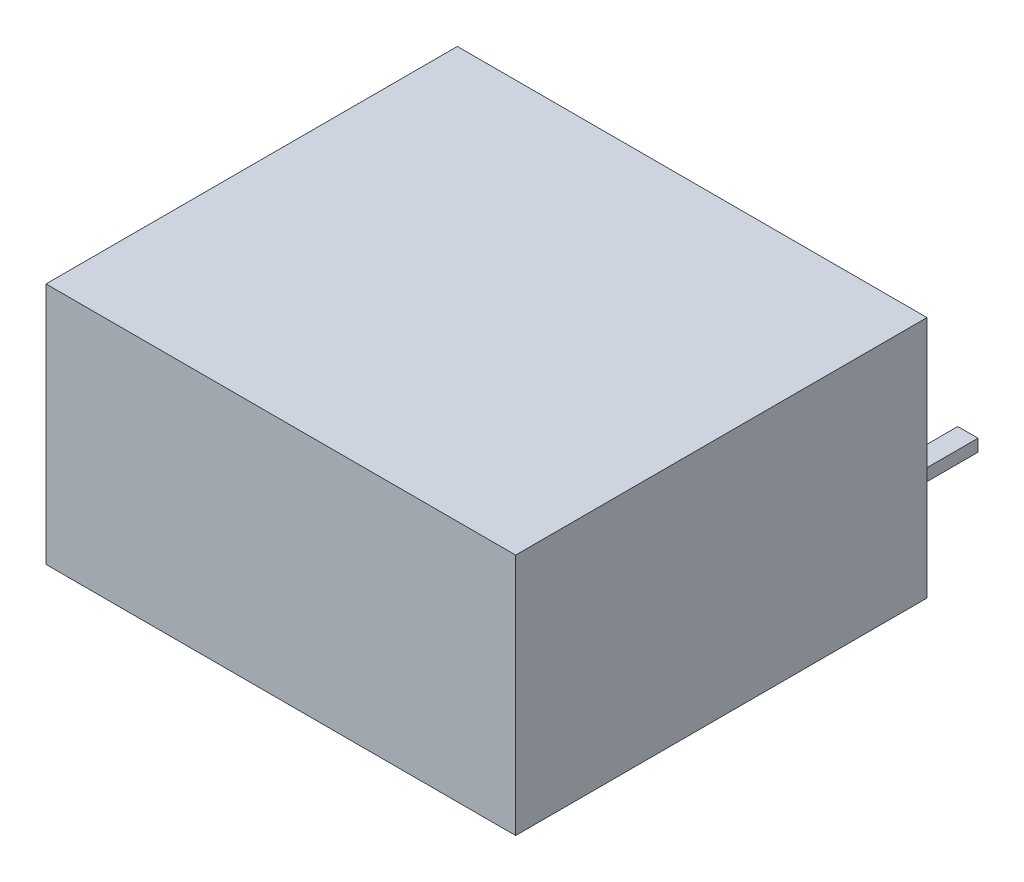
SolidWorks part; units mm, degrees
other "Детальный элемент1"
ref_plane "Спереди" through (0, 0, 0) normal (0, 0, 1) x (1, 0, 0)
ref_plane "Сверху" through (0, 0, 0) normal (0, 1, 0) x (1, 0, 0)
ref_plane "Справа" through (0, 0, 0) normal (1, 0, 0) x (0, 0, -1)
sketch "Эскиз1" plane through (0, 0, 0) normal (0, 0, 1) x (1, 0, 0)
  line L1 (-5.8, -3) -> (5.8, -3)
  line L2 (-5.8, -3) -> (-5.8, 3)
  line L3 (-5.8, 3) -> (5.8, 3)
  line L4 (5.8, -3) -> (5.8, 3)
  line L5 (-5.8, -3) -> (5.8, 3) construction
  line L6 (-5.8, 3) -> (5.8, -3) construction
  point P0 (0, 0)
  dimension "D1" = 11.6
  dimension "D2" = 6
extrude "Бобышка-Вытянуть1" add sketch "Эскиз1" along normal blind 10.16
sketch "Эскиз2" plane through (0, 0, 0) normal (0, 0, -1) x (-1, 0, 0)
  line L0 (5.8, -3) -> (-5.8, -3) construction
  line L1 (1.02, -2.25) -> (1.52, -2.25)
  line L2 (1.02, -2.25) -> (1.02, -1.95)
  line L3 (1.02, -1.95) -> (1.52, -1.95)
  line L4 (1.52, -2.25) -> (1.52, -1.95)
  line L5 (1.02, -2.25) -> (1.52, -1.95) construction
  line L6 (1.02, -1.95) -> (1.52, -2.25) construction
  point P0 (1.27, -2.1)
  point P6 (0, 0)
  dimension "D1" = 1.27
  dimension "D2" = 0.9
  dimension "D3" = 0.3
  dimension "D4" = 0.5
extrude "Бобышка-Вытянуть2" add sketch "Эскиз2" along normal blind 3 separate body
pattern_linear "Линейный массив1" count 2 spacing 2.54 along (-1, 0, 0) count 3 spacing 2.54 along (1, 0, 0) of bodies 108
